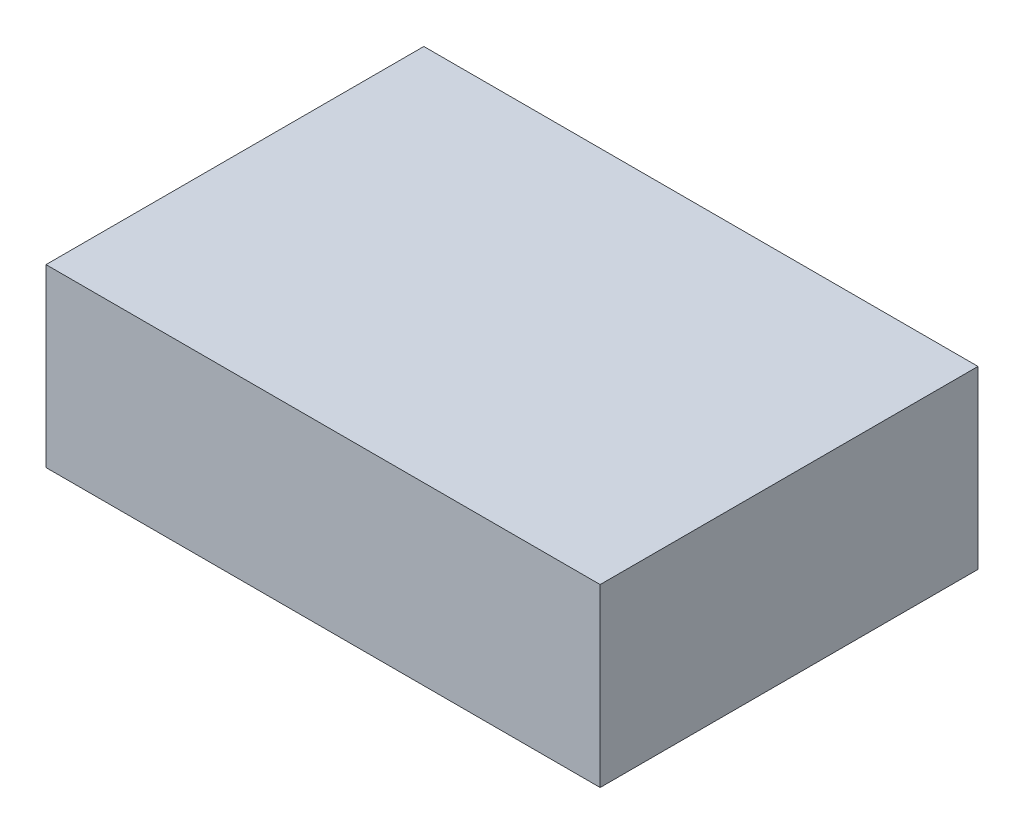
SolidWorks part; units mm, degrees
ref_plane "Спереди" through (0, 0, 0) normal (0, 0, 1) x (1, 0, 0)
ref_plane "Сверху" through (0, 0, 0) normal (0, 1, 0) x (1, 0, 0)
ref_plane "Справа" through (0, 0, 0) normal (1, 0, 0) x (0, 0, -1)
other "Configuration Table"
sketch "Эскиз1" plane through (0, 0, 0) normal (0, 1, 0) x (1, 0, 0)
  line L1 (0, 0) -> (31.5236, 0)
  line L2 (0, 0) -> (0, 21.4934)
  line L3 (0, 21.4934) -> (31.5236, 21.4934)
  line L4 (31.5236, 0) -> (31.5236, 21.4934)
extrude "Бобышка-Вытянуть1" add sketch "Эскиз1" along normal blind 10
